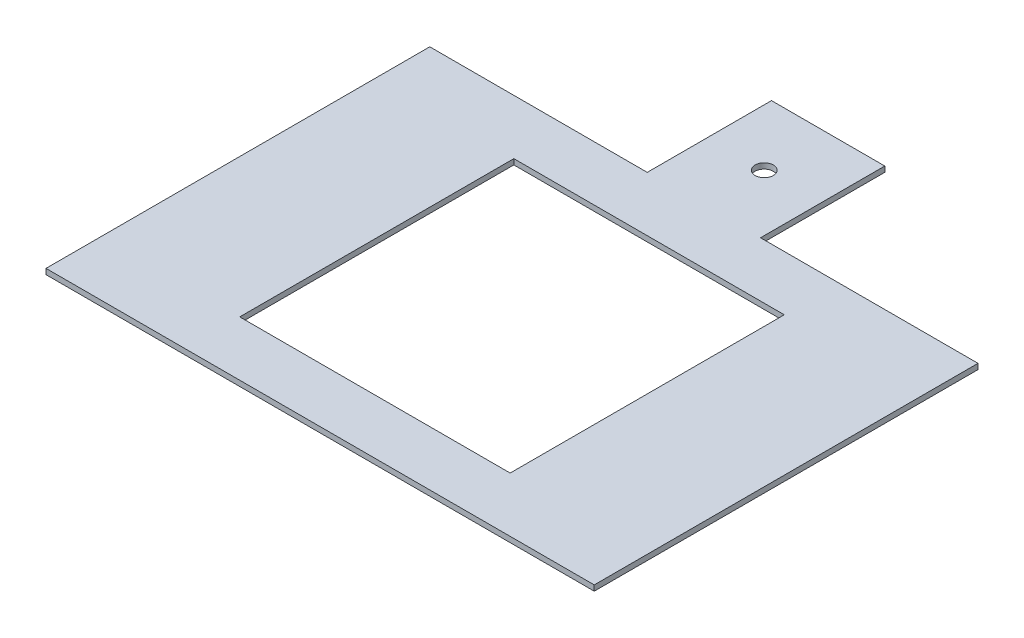
SolidWorks part; units mm, degrees
ref_plane "Front" through (0, 0, 0) normal (0, 0, 1) x (1, 0, 0)
ref_plane "Top" through (0, 0, 0) normal (0, 1, 0) x (1, 0, 0)
ref_plane "Right" through (0, 0, 0) normal (1, 0, 0) x (0, 0, -1)
sketch "Sketch1" plane through (0, 0, 0) normal (0, 1, 0) x (1, 0, 0)
  line L1 (-74, -75) -> (74, -75)
  line L2 (-74, -75) -> (-74, 75)
  line L3 (-74, 75) -> (74, 75)
  line L4 (74, -75) -> (74, 75)
  line L5 (-74, -75) -> (74, 75) construction
  line L6 (-74, 75) -> (74, -75) construction
  line L7 (-150, -105) -> (150, -105)
  line L8 (-150, -105) -> (-150, 105)
  line L9 (-150, 105) -> (150, 105)
  line L10 (150, -105) -> (150, 105)
  line L11 (-150, -105) -> (150, 105) construction
  line L12 (-150, 105) -> (150, -105) construction
  point P0 (0, 0)
  point P6 (0, 0)
  dimension "D1" = 148
  dimension "D2" = 150
  dimension "D3" = 300
  dimension "D4" = 210
extrude "Boss-Extrude1" add sketch "Sketch1" along normal mid plane 3
sketch "Sketch2" plane through (0, 1.5, 0) normal (0, 1, 0) x (1, 0, 0)
  line L0 (150, 105) -> (-150, 105) construction
  line L1 (31, 105) -> (-31, 105)
  line L2 (31, 105) -> (31, 173)
  line L3 (31, 173) -> (-31, 173)
  line L4 (-31, 105) -> (-31, 173)
  line L5 (0, -50) -> (0, 50) construction
  line L6 (0, 0) -> (0, 222.8351) construction
  circle A0 centre (0, 138) radius 5
  point P13 (0, 0)
  dimension "D1" = 10
  dimension "D2" = 138
  dimension "D3" = 35
  dimension "D4" = 62
extrude "Boss-Extrude2" add sketch "Sketch2" against normal through all
